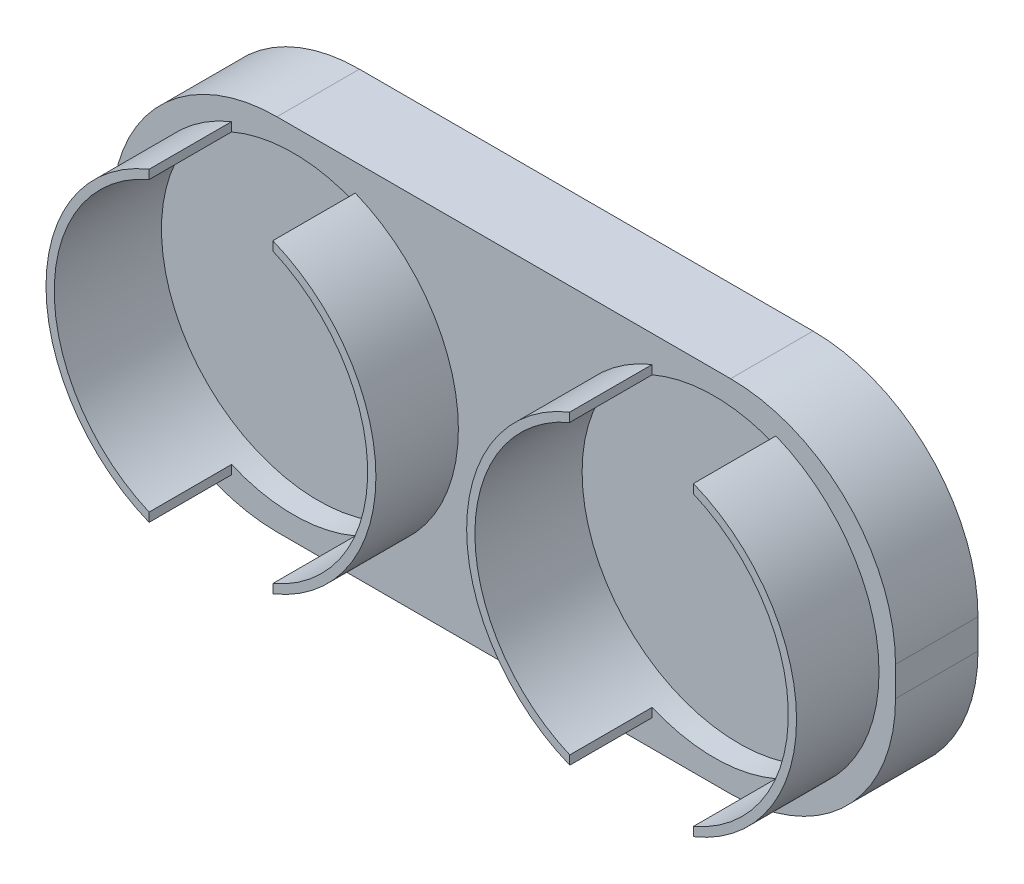
SolidWorks part; units mm, degrees
ref_plane "Front Plane" through (0, 0, 0) normal (1, 0, 0) x (0, 1, 0)
ref_plane "Top Plane" through (0, 0, 0) normal (0, 0, 1) x (0, 1, 0)
ref_plane "Right Plane" through (0, 0, 0) normal (0, 1, 0) x (-1, 0, 0)
sketch "Sketch1" plane through (0, 0, 0) normal (0, 0, 1) x (0, 1, 0)
  line L1 (-21.8, -47.5) -> (21.8, -47.5)
  line L2 (-21.8, -47.5) -> (-21.8, 47.5)
  line L3 (-21.8, 47.5) -> (21.8, 47.5)
  line L4 (21.8, -47.5) -> (21.8, 47.5)
  line L5 (-21.8, -47.5) -> (21.8, 47.5) construction
  line L6 (-21.8, 47.5) -> (21.8, -47.5) construction
  point P0 (0, 0)
extrude "Boss-Extrude1" add sketch "Sketch1" along normal blind 10
sketch "Sketch2" plane through (0, 0, 0) normal (0, 0, -1) x (1, 0, 0)
  line L0 (0, 21.8) -> (0, -21.8) construction
  line L1 (-47.5, 21.8) -> (47.5, 21.8) construction
  line L2 (47.5, -21.8) -> (-47.5, -21.8) construction
  line L3 (-47.5, 0) -> (47.5, 0) construction
  line L4 (-47.5, -21.8) -> (-47.5, 21.8) construction
  line L5 (47.5, 21.8) -> (47.5, -21.8) construction
  line L6 (0, 8.55) -> (0, 0)
  circle A0 centre (0, 12.45) radius 3.9
  circle A1 centre (0, -12.45) radius 3.9
  dimension "D1" = 7.8
extrude "Boss-Extrude2" add sketch "Sketch2" along normal blind 4 contours A0 | A1
sketch "Sketch5" plane through (0, 0, 10) normal (0, 0, 1) x (1, 0, 0)
  line L0 (-47.5, 0) -> (47.5, 0) construction
  line L1 (-47.5, 21.8) -> (-47.5, -21.8) construction
  line L2 (47.5, -21.8) -> (47.5, 21.8) construction
  line L3 (0, 21.8) -> (0, -21.8) construction
  line L4 (47.5, 21.8) -> (-47.5, 21.8) construction
  line L5 (-47.5, -21.8) -> (47.5, -21.8) construction
  line L6 (-47.5, 0) -> (-45.5, 0)
  circle A0 centre (-25.5, 0) radius 19
  circle A1 centre (-25.5, 0) radius 20
  circle A2 centre (25.5, 0) radius 20
  circle A3 centre (25.5, 0) radius 19
  dimension "D1" = 38
  dimension "D2" = 1
extrude "Boss-Extrude4" add sketch "Sketch5" along normal blind 10 contours A1 A0 | A2 A3
sketch "Sketch6" plane through (0, 0, 20) normal (0, 0, 1) x (1, 0, 0)
  line L1 (-33, -21.8) -> (-18, -21.8)
  line L2 (-33, -21.8) -> (-33, 21.8)
  line L3 (-33, 21.8) -> (-18, 21.8)
  line L4 (-18, -21.8) -> (-18, 21.8)
  line L5 (-33, -21.8) -> (-18, 21.8) construction
  line L6 (-33, 21.8) -> (-18, -21.8) construction
  line L7 (47.5, 21.8) -> (-47.5, 21.8) construction
  line L8 (0, 21.8) -> (0, -21.8) construction
  line L9 (-47.5, -21.8) -> (47.5, -21.8) construction
  line L10 (33, 21.8) -> (18, -21.8) construction
  line L11 (33, -21.8) -> (18, 21.8) construction
  line L12 (18, -21.8) -> (18, 21.8)
  line L13 (33, 21.8) -> (18, 21.8)
  line L14 (33, -21.8) -> (33, 21.8)
  line L15 (33, -21.8) -> (18, -21.8)
  point P0 (-25.5, 0)
  point P17 (25.5, 0)
  dimension "D1" = 43.6
  dimension "D2" = 15
extrude "Cut-Extrude1" cut sketch "Sketch6" against normal up to surface (10 mm away) up to face at (45.5, 0, 10)
fillet "Fillet1" radius 20 4 edges at (-47.5, 21.8, 5) (-47.5, -21.8, 5) (47.5, -21.8, 5) (47.5, 21.8, 5)
sketch "Sketch7" plane through (0, 0, 10) normal (0, 0, 1) x (1, 0, 0)
  line L0 (0, 21.8) -> (0, -21.8) construction
  line L1 (27.5, 21.8) -> (-27.5, 21.8) construction
  line L2 (-27.5, -21.8) -> (27.5, -21.8) construction
  circle A0 centre (-25.5, 0) radius 19
  circle A1 centre (25.5, 0) radius 19
extrude "Cut-Extrude2" cut sketch "Sketch7" against normal blind 3
